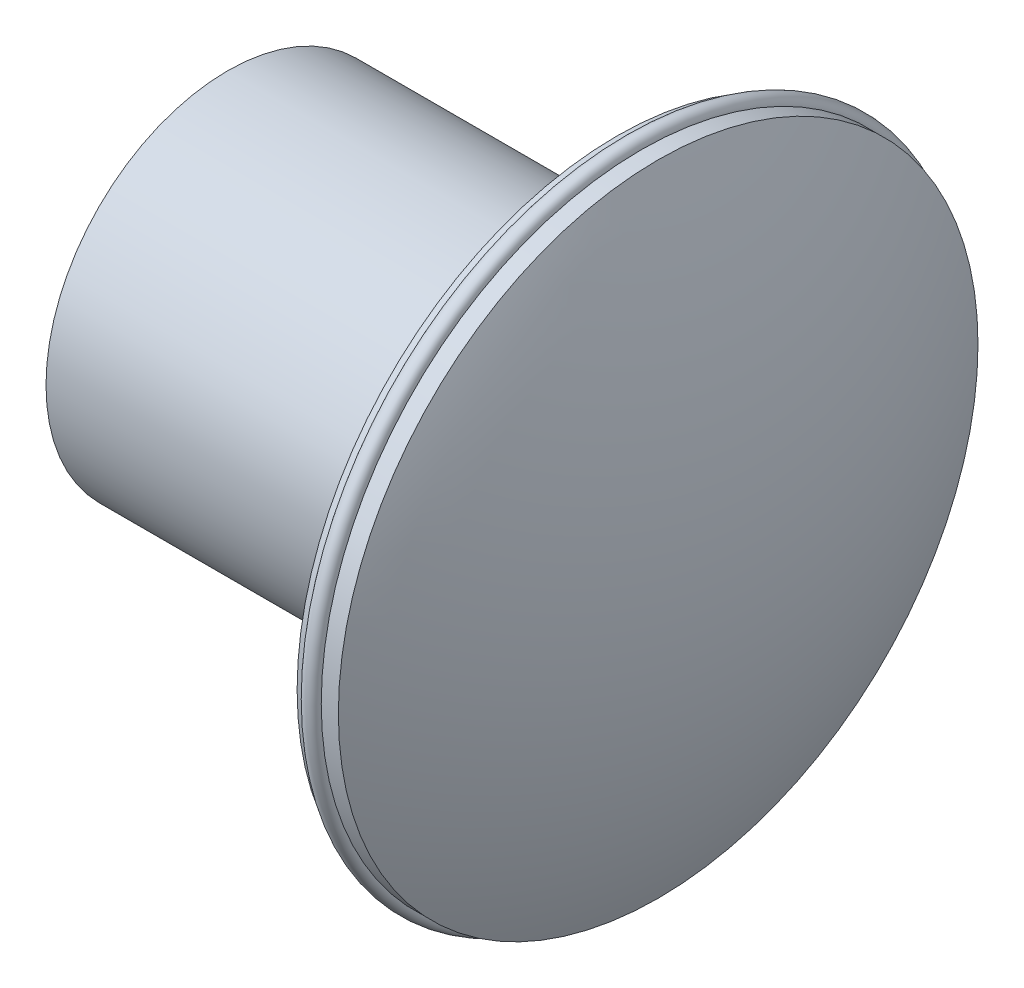
SolidWorks part; units mm, degrees
ref_plane "Front Plane" through (0, 0, 0) normal (0, 0, 1) x (1, 0, 0)
ref_plane "Top Plane" through (0, 0, 0) normal (0, 1, 0) x (1, 0, 0)
ref_plane "Right Plane" through (0, 0, 0) normal (1, 0, 0) x (0, 0, -1)
sketch "Sketch1" plane through (0, 0, 0) normal (0, 0, 1) x (1, 0, 0)
  line L0 (-76.8401, 0) -> (0, 0) construction
  line L1 (38.1, 0) -> (38.1, 28.2977)
  line L2 (26.8313, 16.0646) -> (34.4513, 28.2977)
  line L3 (34.4513, 28.2977) -> (35.1186, 28.2977)
  line L4 (36.5855, 28.2977) -> (38.1, 28.2977)
  line L6 (26.8313, 16.0646) -> (0, 16.0646)
  line L7 (0, 16.0646) -> (0, 0)
  line L8 (38.1, 0) -> (0, 0)
  arc A0 (35.1186, 28.2977) -> (36.5855, 28.2977) centre (35.852, 28.2977) cw
  dimension "D2" = 7.62
sketch "Sketch4" plane through (0, 0, 0) normal (0, 1, 0) x (1, 0, 0)
revolve "Revolve4" add sketch "Sketch1" angle 360 about L0
sketch "Sketch9" plane through (0, 0, 0) normal (0, 0, 1) x (1, 0, 0)
  line L0 (0, 0) -> (38.1, 0)
  dimension "D1" = 38.1
sketch "Sketch10" plane through (38.1, 0, 0) normal (1, 0, 0) x (0, 0, -1)
  circle A0 centre (0, 0) radius 28.2977
sketch "Sketch11" plane through (0, 0, 0) normal (0, 0, 1) x (1, 0, 0)
  line L0 (38.1, 0) -> (44.45, 0) construction
  line L1 (38.1, 28.2977) -> (38.1, 0)
  line L2 (38.1, 0) -> (44.45, 0)
  arc A0 (44.45, 0) -> (38.1, 28.2977) centre (-21.7771, 0) ccw
revolve "Revolve7" add sketch "Sketch11" angle 360 about L0
